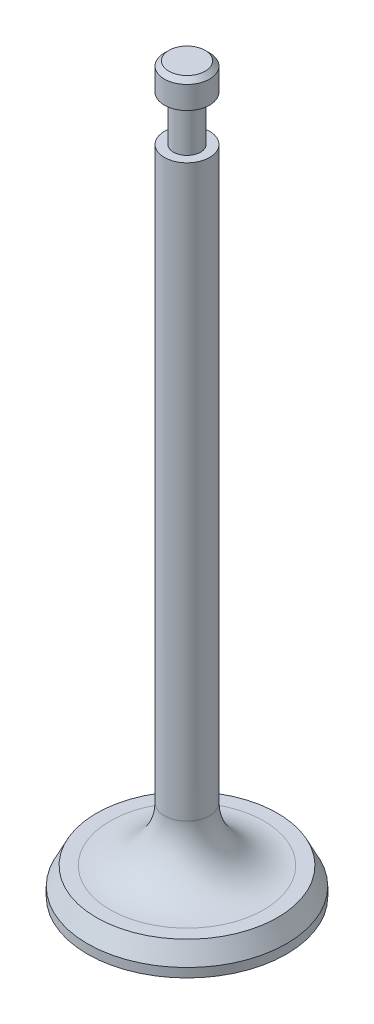
SolidWorks part; units mm, degrees
material "Titanium"
ref_plane "Front Plane" through (0, 0, 0) normal (0, 0, 1) x (1, 0, 0)
ref_plane "Top Plane" through (0, 0, 0) normal (0, 1, 0) x (1, 0, 0)
ref_plane "Right Plane" through (0, 0, 0) normal (1, 0, 0) x (0, 0, -1)
sketch "Sketch1" plane through (0, 0, 0) normal (1, 0, 0) x (0, 0, -1)
  line L0 (0, 0) -> (0, -80)
  line L1 (0, -80) -> (11, -80)
  line L2 (11, -80) -> (11, -77)
  line L3 (11, -77) -> (2.5, -77)
  line L4 (2.5, -77) -> (2.5, -8)
  line L5 (2.5, -8) -> (1.5, -8)
  line L6 (1.5, -8) -> (1.5, -3)
  line L7 (1.5, -3) -> (2.5, -3)
  line L8 (2.5, -3) -> (2.5, 0)
  line L9 (2.5, 0) -> (0, 0)
  dimension "D1" = 80
  dimension "D2" = 3
  dimension "D3" = 2.5
  dimension "D4" = 3
  dimension "D5" = 5
  dimension "D6" = 1
  dimension "D7" = 11
revolve "Revolve1" add sketch "Sketch1" angle 360 about L0
fillet "Fillet1" radius 6 1 edges at (0, -77, -2.5)
chamfer "Chamfer1" distance 1 distance2 2 1 edges at (0, -77, -11)
chamfer "Chamfer2" distance 0.5 angle 45 1 edges at (0, 0, -2.5)
